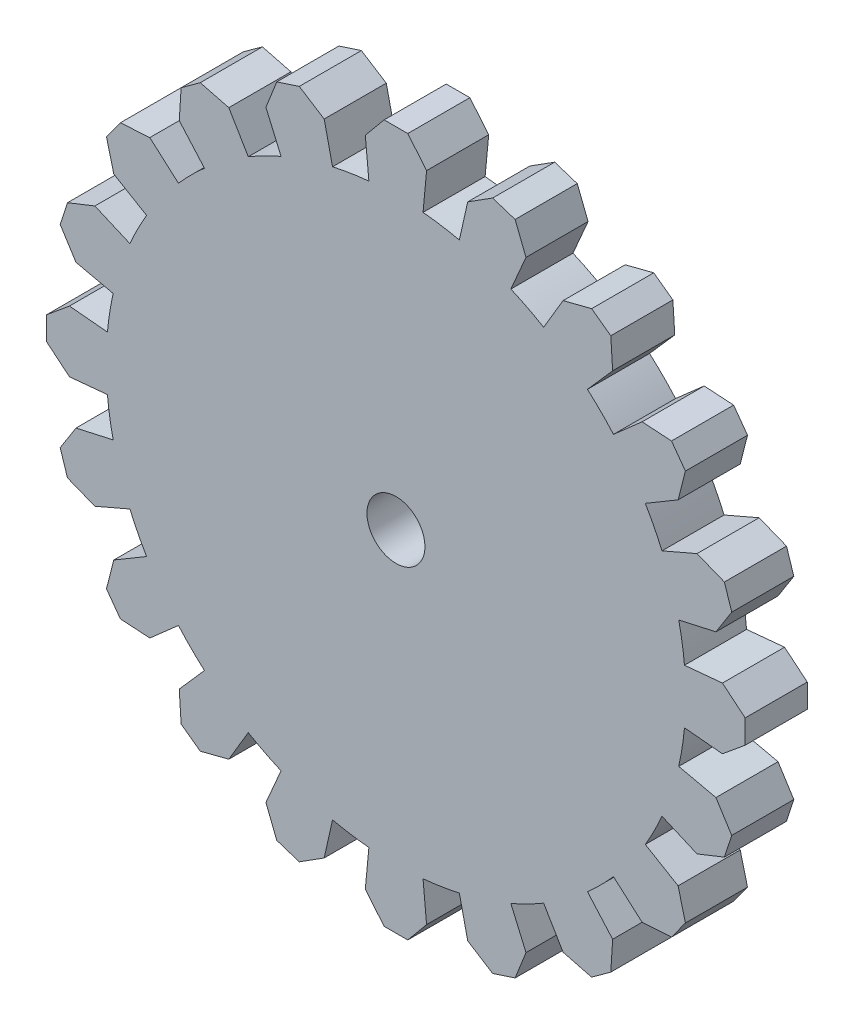
SolidWorks part; units mm, degrees
ref_plane "Front Plane" through (0, 0, 0) normal (0, 0, 1) x (1, 0, 0)
ref_plane "Top Plane" through (0, 0, 0) normal (0, 1, 0) x (1, 0, 0)
ref_plane "Right Plane" through (0, 0, 0) normal (1, 0, 0) x (0, 0, -1)
sketch "Sketch1" plane through (0, 0, 0) normal (0, 0, 1) x (1, 0, 0)
  circle A0 centre (0, 0) radius 70
  dimension "D1" = 140
extrude "Boss-Extrude1" add sketch "Sketch1" along normal blind 15
sketch "Sketch2" plane through (0, 0, 0) normal (0, 0, 1) x (1, 0, 0)
  circle A0 centre (0, 0) radius 7
  dimension "D1" = 14
extrude "Cut-Extrude5" cut sketch "Sketch2" against normal through all and the other way blind 55 contours A0
sketch "Sketch5" plane through (0, 0, 0) normal (0, 0, 1) x (1, 0, 0)
  line L0 (0, 0) -> (0, 110.8429) construction
  line L1 (-6.54, 69.6938) -> (-7.4005, 78.8642)
  line L2 (-7.4005, 78.8642) -> (-2.8567, 84.3491)
  line L3 (-2.8567, 84.3491) -> (2.8567, 84.3491)
  line L4 (6.54, 69.6938) -> (7.4005, 78.8642)
  line L5 (7.4005, 78.8642) -> (2.8567, 84.3491)
  line L6 (-6.54, 69.6938) -> (-6.5262, 69.5744)
  line L7 (-6.5262, 69.5744) -> (-6.526, 69.5724)
  line L8 (6.54, 69.6938) -> (6.5382, 69.6753)
  line L9 (-6.5262, 69.5744) -> (-1.9858, 69.9718)
  line L10 (-1.9858, 69.9718) -> (6.5382, 69.6753)
  circle A0 centre (0, 0) radius 70 construction
  point P12 (0, 84.3491)
extrude "Boss-Extrude2" add sketch "Sketch5" along normal blind 15 contours L6 L1 L2 L3 L5 L4 L8 L10 L9
sketch "Sketch6" plane through (0, 0, 0) normal (0, 0, 1) x (1, 0, 0)
  line L0 (0, 0) -> (0, 120.775) construction
pattern_circular "CirPattern2" count 20 over 360 about axis through (0, 0, 0) along (0, 0, 1) of "Boss-Extrude2"
